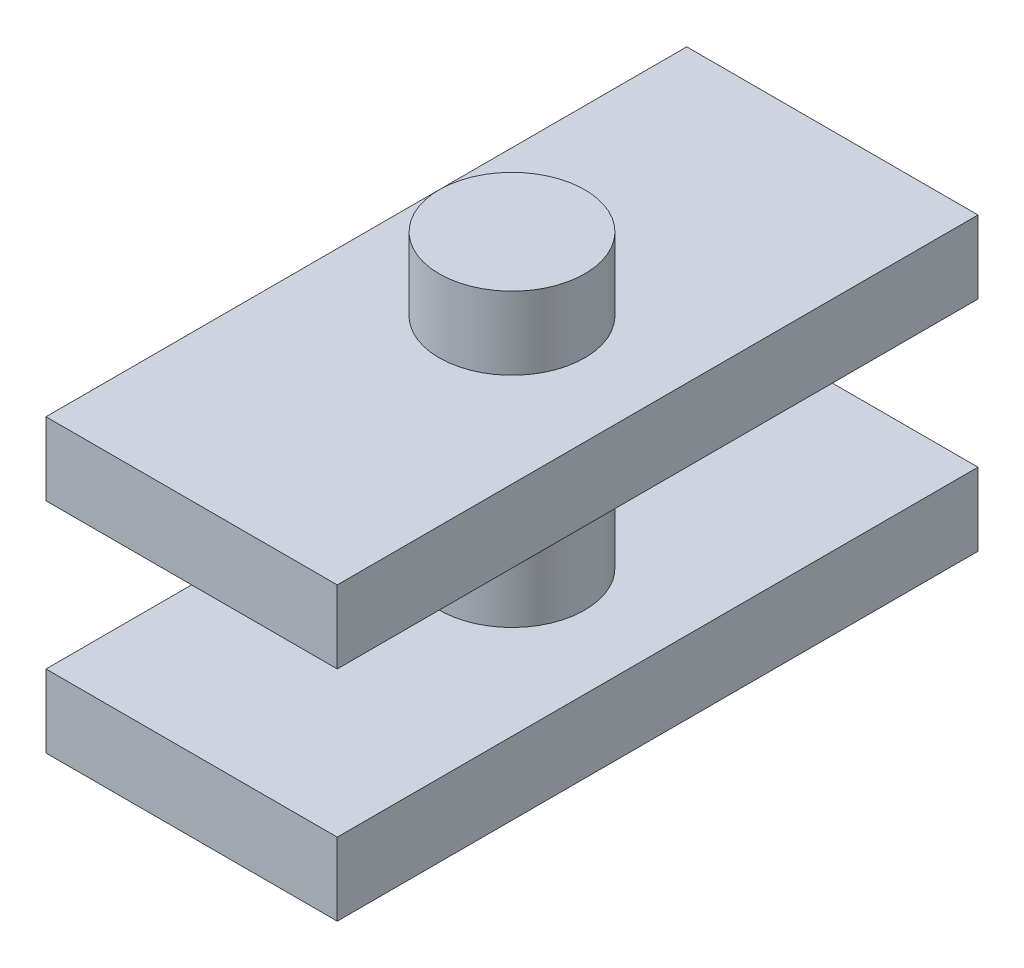
SolidWorks part; units mm, degrees
ref_plane "Front Plane" through (0, 0, 0) normal (0, 0, 1) x (1, 0, 0)
ref_plane "Top Plane" through (0, 0, 0) normal (0, 1, 0) x (1, 0, 0)
ref_plane "Right Plane" through (0, 0, 0) normal (1, 0, 0) x (0, 0, -1)
sketch "Sketch1" plane through (0, 0, 0) normal (0, 1, 0) x (1, 0, 0)
  circle A0 centre (0, 0) radius 5
extrude "Boss-Extrude1" add sketch "Sketch1" along normal blind 30
sketch "Sketch2" plane through (0, 30, 0) normal (0, 1, 0) x (1, 0, 0)
  line L1 (-10, -22) -> (10, -22)
  line L3 (-10, 22) -> (10, 22)
  line L4 (-10, 22) -> (-10, -22)
  line L5 (10, 22) -> (10, -22)
  dimension "D1" = 20
extrude "Boss-Extrude2" add sketch "Sketch2" against normal blind 10
sketch "Sketch3" plane through (0, 30, 0) normal (0, 1, 0) x (1, 0, 0)
  line L1 (-10, 22) -> (10, 22)
  line L2 (-10, 22) -> (-10, -22)
  line L3 (-10, -22) -> (10, -22)
  line L4 (10, 22) -> (10, -22)
  circle A0 centre (0, 0) radius 5
sketch "Sketch4" plane through (0, 30, 0) normal (0, 1, 0) x (1, 0, 0)
  line L1 (-10, 22) -> (10, 22)
  line L2 (-10, 22) -> (-10, -22)
  line L3 (-10, -22) -> (10, -22)
  line L4 (10, 22) -> (10, -22)
  circle A0 centre (0, 0) radius 5
extrude "Cut-Extrude2" cut sketch "Sketch4" against normal blind 5
ref_plane "Plane1" through (0, 15, 0) normal (0, -1, 0) x (-1, 0, 0)
mirror "Mirror2" about plane through (0, 15, 0) normal (0, -1, 0) of "Cut-Extrude2", "Boss-Extrude2"
